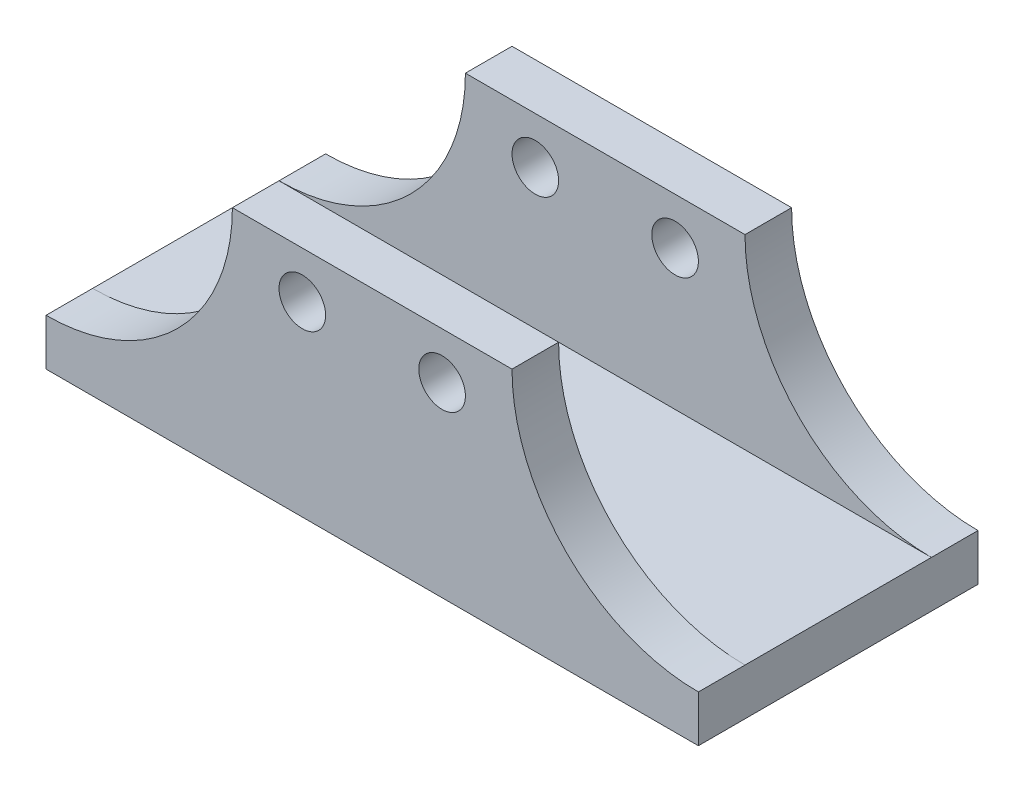
SolidWorks part; units mm, degrees
ref_plane "Ön Düzlem" through (0, 0, 0) normal (0, 0, 1) x (1, 0, 0)
ref_plane "Üst Düzlem" through (0, 0, 0) normal (0, 1, 0) x (1, 0, 0)
ref_plane "Sağ Düzlem" through (0, 0, 0) normal (1, 0, 0) x (0, 0, -1)
sketch "Çizim2" plane through (0, 0, 0) normal (0, 0, 1) x (1, 0, 0)
  line L0 (-49.1372, 3.9225) -> (-49.1372, -6.0775)
  line L1 (-49.1372, -6.0775) -> (90.8628, -6.0775)
  line L2 (90.8628, -6.0775) -> (90.8628, 3.9225)
  line L5 (-9.1372, 43.9225) -> (50.8628, 43.9225)
  arc A0 (-49.1372, 3.9225) -> (-9.1372, 43.9225) centre (-49.1372, 43.9225) ccw
  arc A1 (50.8628, 43.9225) -> (90.8628, 3.9225) centre (90.8628, 43.9225) ccw
  circle A2 centre (5.8628, 33.9225) radius 5
  circle A3 centre (35.8628, 33.9225) radius 5
extrude "Yükseklik-Ekstrüzyon2" add sketch "Çizim2" along normal blind 10
sketch "Çizim3" plane through (0, 0, 10) normal (0, 0, 1) x (1, 0, 0)
  line L0 (-49.1372, 3.9225) -> (90.8628, 3.9225)
  line L1 (90.8628, 3.9225) -> (90.8628, -6.0775)
  line L2 (90.8628, -6.0775) -> (-49.1372, -6.0775)
  line L3 (-49.1372, -6.0775) -> (-49.1372, 3.9225)
  arc A0 (-49.1372, 3.9225) -> (-9.1372, 43.9225) centre (-49.1372, 43.9225) ccw construction
extrude "Yükseklik-Ekstrüzyon3" add sketch "Çizim3" along normal blind 40
sketch "Çizim4" plane through (0, 0, 50) normal (0, 0, 1) x (1, 0, 0)
  line L0 (-49.1372, 3.9225) -> (-49.1372, -6.0775)
  line L1 (-49.1372, -6.0775) -> (90.8628, -6.0775)
  line L2 (-9.1372, 43.9225) -> (50.8628, 43.9225)
  line L3 (90.8628, -6.0775) -> (90.8628, 3.9225)
  arc A0 (-49.1372, 3.9225) -> (-9.1372, 43.9225) centre (-49.1372, 43.9225) ccw
  arc A1 (50.8628, 43.9225) -> (90.8628, 3.9225) centre (90.8628, 43.9225) ccw
  circle A2 centre (5.8628, 33.9225) radius 5
  circle A3 centre (35.8628, 33.9225) radius 5
extrude "Yükseklik-Ekstrüzyon4" add sketch "Çizim4" along normal blind 10
sketch "Çizim5" plane through (0, 3.9225, 0) normal (0, 1, 0) x (1, 0, 0)
  circle A0 centre (20.8628, -30) radius 5
extrude "Kes-Ekstrüzyon1" cut sketch "Çizim5" against normal blind 10
